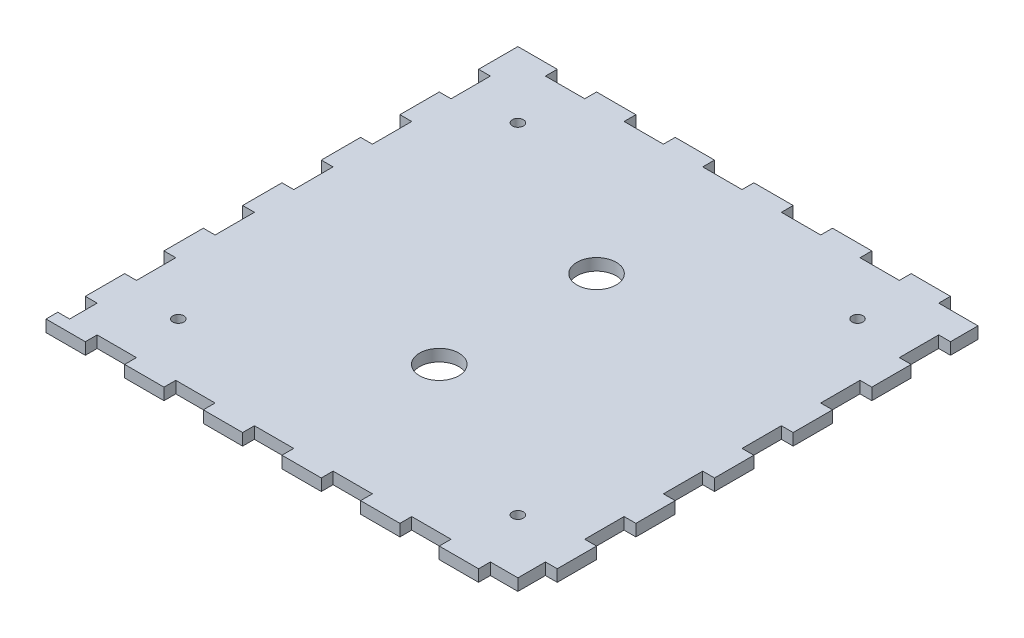
SolidWorks part; units mm, degrees
material "Beech"
ref_plane "Front Plane" through (0, 0, 0) normal (0, 0, 1) x (1, 0, 0)
ref_plane "Top Plane" through (0, 0, 0) normal (0, 1, 0) x (1, 0, 0)
ref_plane "Right Plane" through (0, 0, 0) normal (1, 0, 0) x (0, 0, -1)
sketch "Sketch1" plane through (0, 0, 0) normal (0, 1, 0) x (1, 0, 0)
  line L1 (-55.1817, 59.3802) -> (64.8183, 59.3802)
  line L2 (-55.1817, 59.3802) -> (-55.1817, -60.6198)
  line L3 (-55.1817, -60.6198) -> (64.8183, -60.6198)
  line L4 (64.8183, 59.3802) -> (64.8183, -60.6198)
  line L8 (-45.1817, 59.3802) -> (-45.1817, 56.3802)
  line L9 (-45.1817, 56.3802) -> (-35.1817, 56.3802)
  line L10 (-35.1817, 56.3802) -> (-35.1817, 59.3802)
  line L11 (-15.1817, 56.3802) -> (-15.1817, 59.3802)
  line L12 (-25.1817, 56.3802) -> (-15.1817, 56.3802)
  line L13 (-25.1817, 59.3802) -> (-25.1817, 56.3802)
  line L14 (4.8183, 56.3802) -> (4.8183, 59.3802)
  line L15 (-5.1817, 56.3802) -> (4.8183, 56.3802)
  line L16 (-5.1817, 59.3802) -> (-5.1817, 56.3802)
  line L17 (24.8183, 56.3802) -> (24.8183, 59.3802)
  line L18 (14.8183, 56.3802) -> (24.8183, 56.3802)
  line L19 (14.8183, 59.3802) -> (14.8183, 56.3802)
  line L20 (44.8183, 56.3802) -> (44.8183, 59.3802)
  line L21 (34.8183, 56.3802) -> (44.8183, 56.3802)
  line L22 (34.8183, 59.3802) -> (34.8183, 56.3802)
  line L23 (-35.1817, 56.3802) -> (-15.1817, 56.3802) construction
  line L24 (-45.1817, -60.6198) -> (-45.1817, -57.6198)
  line L25 (-45.1817, -57.6198) -> (-35.1817, -57.6198)
  line L26 (-35.1817, -57.6198) -> (-35.1817, -60.6198)
  line L27 (-15.1817, -57.6198) -> (-15.1817, -60.6198)
  line L28 (-25.1817, -57.6198) -> (-15.1817, -57.6198)
  line L29 (-25.1817, -60.6198) -> (-25.1817, -57.6198)
  line L30 (4.8183, -57.6198) -> (4.8183, -60.6198)
  line L31 (-5.1817, -57.6198) -> (4.8183, -57.6198)
  line L32 (-5.1817, -60.6198) -> (-5.1817, -57.6198)
  line L33 (24.8183, -57.6198) -> (24.8183, -60.6198)
  line L34 (14.8183, -57.6198) -> (24.8183, -57.6198)
  line L35 (14.8183, -60.6198) -> (14.8183, -57.6198)
  line L36 (44.8183, -57.6198) -> (44.8183, -60.6198)
  line L37 (34.8183, -57.6198) -> (44.8183, -57.6198)
  line L38 (34.8183, -60.6198) -> (34.8183, -57.6198)
  line L39 (-35.1817, -57.6198) -> (-15.1817, -57.6198) construction
  line L40 (-55.1817, 49.3802) -> (-52.1817, 49.3802)
  line L41 (-52.1817, 49.3802) -> (-52.1817, 39.3802)
  line L42 (-52.1817, 39.3802) -> (-55.1817, 39.3802)
  line L43 (-52.1817, 19.3802) -> (-55.1817, 19.3802)
  line L44 (-52.1817, 29.3802) -> (-52.1817, 19.3802)
  line L45 (-55.1817, 29.3802) -> (-52.1817, 29.3802)
  line L46 (-52.1817, -0.6198) -> (-55.1817, -0.6198)
  line L47 (-52.1817, 9.3802) -> (-52.1817, -0.6198)
  line L48 (-55.1817, 9.3802) -> (-52.1817, 9.3802)
  line L49 (-52.1817, -20.6198) -> (-55.1817, -20.6198)
  line L50 (-52.1817, -10.6198) -> (-52.1817, -20.6198)
  line L51 (-55.1817, -10.6198) -> (-52.1817, -10.6198)
  line L52 (-52.1817, -40.6198) -> (-55.1817, -40.6198)
  line L53 (-52.1817, -30.6198) -> (-52.1817, -40.6198)
  line L54 (-55.1817, -30.6198) -> (-52.1817, -30.6198)
  line L55 (64.8183, 49.3802) -> (61.8183, 49.3802)
  line L56 (61.8183, 49.3802) -> (61.8183, 39.3802)
  line L57 (61.8183, 39.3802) -> (64.8183, 39.3802)
  line L58 (61.8183, 19.3802) -> (64.8183, 19.3802)
  line L59 (61.8183, 29.3802) -> (61.8183, 19.3802)
  line L60 (64.8183, 29.3802) -> (61.8183, 29.3802)
  line L61 (61.8183, -0.6198) -> (64.8183, -0.6198)
  line L62 (61.8183, 9.3802) -> (61.8183, -0.6198)
  line L63 (64.8183, 9.3802) -> (61.8183, 9.3802)
  line L64 (61.8183, -20.6198) -> (64.8183, -20.6198)
  line L65 (61.8183, -10.6198) -> (61.8183, -20.6198)
  line L66 (64.8183, -10.6198) -> (61.8183, -10.6198)
  line L67 (61.8183, -40.6198) -> (64.8183, -40.6198)
  line L68 (61.8183, -30.6198) -> (61.8183, -40.6198)
  line L69 (64.8183, -30.6198) -> (61.8183, -30.6198)
  line L70 (64.8183, 56.3802) -> (64.8183, 59.3802)
  line L71 (54.8183, 56.3802) -> (64.8183, 56.3802)
  line L72 (54.8183, 59.3802) -> (54.8183, 56.3802)
  line L73 (-52.1817, -60.6198) -> (-55.1817, -60.6198)
  line L74 (-52.1817, -50.6198) -> (-52.1817, -60.6198)
  line L75 (-55.1817, -50.6198) -> (-52.1817, -50.6198)
  line L76 (64.8183, -57.6198) -> (64.8183, -60.6198)
  line L77 (54.8183, -57.6198) -> (64.8183, -57.6198)
  line L78 (54.8183, -60.6198) -> (54.8183, -57.6198)
  line L79 (61.8183, -60.6198) -> (64.8183, -60.6198)
  line L80 (61.8183, -50.6198) -> (61.8183, -60.6198)
  line L81 (64.8183, -50.6198) -> (61.8183, -50.6198)
  line L82 (-52.1817, -57.6198) -> (-55.1817, -57.6198)
  circle A0 centre (-38.3817, -43.7798) radius 1.397
  circle A1 centre (47.9783, -43.7798) radius 1.397
  circle A2 centre (-38.3817, 42.5802) radius 1.397
  circle A3 centre (47.9783, 42.5802) radius 1.397
  circle A4 centre (4.8183, -20.6198) radius 5
  circle A5 centre (4.8183, 19.3802) radius 5
  dimension "D28" = 10
  dimension "D29" = 10
  dimension "D1" = 120
  dimension "D2" = 120
  dimension "D3" = 16.8
  dimension "D4" = 16.84
  dimension "D5" = 16.8
  dimension "D6" = 16.84
  dimension "D7" = 10
  dimension "D8" = 10
  dimension "D9" = 3
  dimension "D11" = 20
  dimension "D12" = 10
  dimension "D13" = 10
  dimension "D14" = 3
  dimension "D16" = 20
  dimension "D17" = 10
  dimension "D18" = 10
  dimension "D19" = 3
  dimension "D21" = 10
  dimension "D22" = 10
  dimension "D23" = 3
  dimension "D25" = 60
  dimension "D26" = 40
  dimension "D27" = 40
  dimension "D10" = 6
  dimension "D15" = 6
  dimension "D20" = 6
  dimension "D24" = 6
extrude "Boss-Extrude1" add sketch "Sketch1" along normal blind 3 contours L69 L4 L64 L65 L66 L61 L62 L63 L58 L59 L60 L57 L56 L55 L1 L20 L21 L22 L17 L18 L19 L14 L15 L16 L11 L12 L13 L10 L9 L8 L2 L40 L41 L42 L45 L44 L43 L48 L47 L46 | L74 L82 L2 L3
sketch "Sketch2" plane through (0, 3, 0) normal (0, 1, 0) x (1, 0, 0)
  text T0 "Back"
  text T1 "Front"
  text T2 "Left"
  text T3 "Right"
